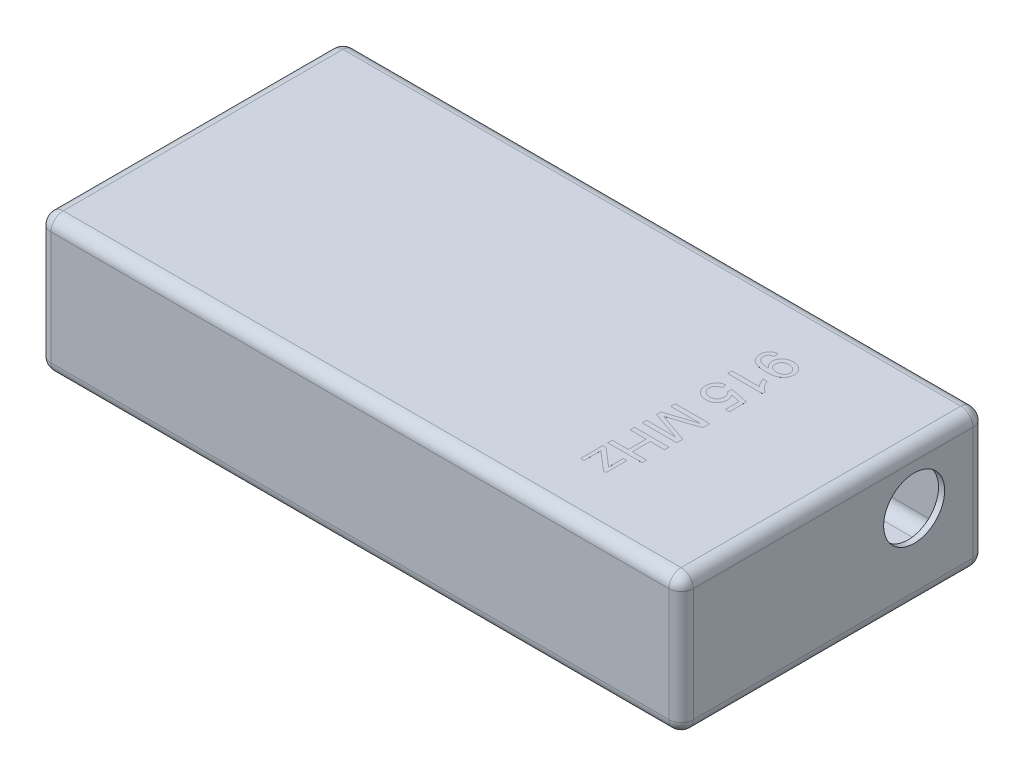
SolidWorks part; units mm, degrees
ref_plane "Front" through (0, 0, 0) normal (0, 0, 1) x (1, 0, 0)
ref_plane "Top" through (0, 0, 0) normal (0, 1, 0) x (1, 0, 0)
ref_plane "Right" through (0, 0, 0) normal (1, 0, 0) x (0, 0, -1)
sketch "Sketch2" plane through (0, 0, 0) normal (0, 1, 0) x (1, 0, 0)
  line L1 (-26.7589, -12.6682) -> (26.7589, -12.6682)
  line L2 (-26.7589, -12.6682) -> (-26.7589, 12.6683)
  line L3 (-26.7589, 12.6683) -> (26.7589, 12.6683)
  line L4 (26.7589, -12.6682) -> (26.7589, 12.6683)
  line L5 (-26.7589, -12.6682) -> (26.7589, 12.6683) construction
  line L6 (-26.7589, 12.6683) -> (26.7589, -12.6682) construction
  point P0 (0, 0)
  dimension "D1" = 53.5178
  dimension "D2" = 25.3365
extrude "Boss-Extrude1" add sketch "Sketch2" along normal mid plane 11.4808
shell "Shell1" thickness 0.508
sketch "Sketch5" plane through (26.7589, 0, 0) normal (1, 0, 0) x (0, 0, -1)
  line L0 (12.6683, 5.7404) -> (12.6683, -5.7404) construction
  line L1 (-12.6682, 5.7404) -> (12.6683, 5.7404) construction
  circle A0 centre (6.7501, 1.3335) radius 2.54
  dimension "D1" = 5.9182
  dimension "D3" = 5.08
  dimension "D2" = 4.4069
extrude "Cut-Extrude1" cut sketch "Sketch5" against normal up to next
sketch "Sketch6" plane through (-26.7589, 0, 0) normal (-1, 0, 0) x (0, 0, 1)
  line L0 (-12.6683, -5.7404) -> (12.6682, -5.7404) construction
  line L1 (-5.08, -4.4704) -> (5.08, -4.4704)
  line L2 (-5.08, -4.4704) -> (-5.08, -0.9144)
  line L3 (-5.08, -0.9144) -> (5.08, -0.9144)
  line L4 (5.08, -4.4704) -> (5.08, -0.9144)
  line L5 (-5.08, -4.4704) -> (5.08, -0.9144) construction
  line L6 (-5.08, -0.9144) -> (5.08, -4.4704) construction
  line L7 (-12.6683, 5.7404) -> (12.6682, 5.7404) construction
  line L8 (-3.81, 1.6764) -> (3.81, 1.6764)
  line L9 (-3.81, 1.6764) -> (-3.81, 4.2164)
  line L10 (-3.81, 4.2164) -> (3.81, 4.2164)
  line L11 (3.81, 1.6764) -> (3.81, 4.2164)
  line L12 (-3.81, 1.6764) -> (3.81, 4.2164) construction
  line L13 (-3.81, 4.2164) -> (3.81, 1.6764) construction
  point P0 (0, -2.6924)
  point P5 (0, 0)
  point P9 (0, 2.9464)
  dimension "D1" = 10.16
  dimension "D2" = 3.556
  dimension "D3" = 1.27
  dimension "D4" = 2.54
  dimension "D5" = 7.62
  dimension "D6" = 1.524
extrude "Cut-Extrude2" [suppressed] cut sketch "Sketch6" against normal up to next
sketch "Sketch7" plane through (0, 5.7404, 0) normal (0, 1, 0) x (1, 0, 0)
  line L0 (13.6779, 12.6683) -> (13.6779, -12.6682) construction
  line L1 (26.7589, 12.6683) -> (-26.7589, 12.6683) construction
  line L2 (-26.7589, -12.6682) -> (26.7589, -12.6682) construction
  line L3 (26.7589, -12.6682) -> (26.7589, 12.6683) construction
  text T0 "915 MHz" font "@Arial Unicode MS" height 2.8702
  dimension "D1" = 13.081
extrude "Boss-Extrude2" add sketch "Sketch7" along normal blind 0.0003
fillet "Fillet1" radius 1.016 22 edges at (0, -5.7404, -12.6683) (-26.7589, -5.7404, 0) (-26.7589, 0, -12.6683) (-26.7589, 0, 12.6682) (0, -5.7404, 12.6682) (26.7589, 0, 12.6682) (26.7589, -5.7404, 0) (26.7589, 0, -12.6683) (26.7589, 5.7404, 0) (0, 5.7404, -12.6683) (-26.7589, 5.7404, 0) (0, 5.7404, 12.6682) (0, 5.2324, 12.1602) (-26.2509, 5.2324, 0) (0, 5.2324, -12.1603) (0, -5.2324, 12.1602) (-26.2509, -5.2324, 0) (0, -5.2324, -12.1603) (26.2509, -5.2324, 0) (26.2509, 5.2324, 0) (26.2509, 0, 12.1602) (26.2509, 0, -12.1603)
